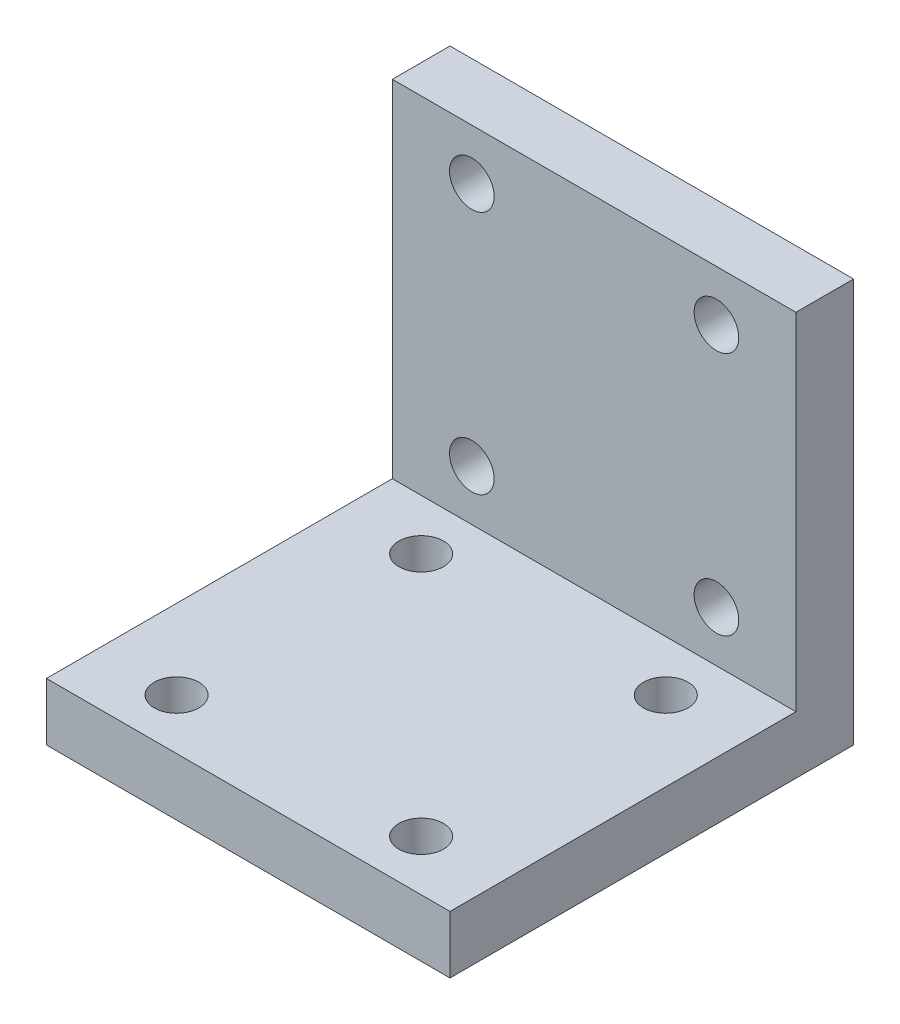
SolidWorks part; units mm, degrees
ref_plane "Front Plane" through (0, 0, 0) normal (0, 0, 1) x (1, 0, 0)
ref_plane "Top Plane" through (0, 0, 0) normal (0, 1, 0) x (1, 0, 0)
ref_plane "Right Plane" through (0, 0, 0) normal (1, 0, 0) x (0, 0, -1)
sketch "Sketch1" plane through (0, 0, 0) normal (1, 0, 0) x (0, 0, -1)
  line L0 (0, 0) -> (44.45, 0)
  line L1 (44.45, 0) -> (44.45, 44.45)
  line L2 (44.45, 44.45) -> (38.1, 44.45)
  line L3 (38.1, 44.45) -> (38.1, 6.35)
  line L4 (38.1, 6.35) -> (0, 6.35)
  line L5 (0, 6.35) -> (0, 0)
  dimension "D1" = 44.45
  dimension "D2" = 6.35
  dimension "D3" = 6.35
extrude "Boss-Extrude1" add sketch "Sketch1" against normal mid plane 44.45
hole_wizard "#10 (0.1935) Diameter Hole1" positions "Sketch4" profile "Sketch3" hole size "#10" standard "ANSI Inch" end condition up to next
sketch "Sketch4" plane through (0, 6.35, 0) normal (0, 1, 0) x (1, 0, 0)
  line L1 (-13.4704, 32.5204) -> (13.4704, 32.5204) construction
  line L2 (-13.4704, 32.5204) -> (-13.4704, 5.5796) construction
  line L3 (-13.4704, 5.5796) -> (13.4704, 5.5796) construction
  line L4 (13.4704, 32.5204) -> (13.4704, 5.5796) construction
  line L5 (-13.4704, 32.5204) -> (13.4704, 5.5796) construction
  line L6 (-13.4704, 5.5796) -> (13.4704, 32.5204) construction
  line L7 (22.225, 38.1) -> (22.225, 0) construction
  line L9 (-22.225, 19.05) -> (22.225, 19.05) construction
  line L10 (-22.225, 38.1) -> (-22.225, 0) construction
  point P2 (13.4704, 5.5796)
  point P73 (-13.4704, 32.5204)
  point P74 (-13.4704, 5.5796)
  point P75 (13.4704, 32.5204)
  point P85 (0, 19.05)
  point P92 (0, 19.05)
  dimension "D1" = 38.1
sketch "Sketch3" plane through (13.4704, 6.35, -5.5796) normal (1, 0, 0) x (0, 0, 1)
  line L0 (0, 0) -> (0, 6.351)
  line L1 (0, 6.351) -> (2.4574, 6.351)
  line L2 (2.4574, 6.351) -> (2.4574, 0)
  line L5 (2.4574, 0) -> (0, 0)
  line L11 (0, -6.35) -> (0, 107.95) construction
  dimension "Thru Hole Dia." = 4.9149
  dimension "Thru Hole Depth" = 6.351
ref_plane "Plane1" through (0, 22.225, -22.225) normal (0, 0.7071, -0.7071) x (-1, 0, 0)
mirror "Mirror1" about plane through (0, 22.225, -22.225) normal (0, 0.7071, -0.7071) of "#10 (0.1935) Diameter Hole1"
